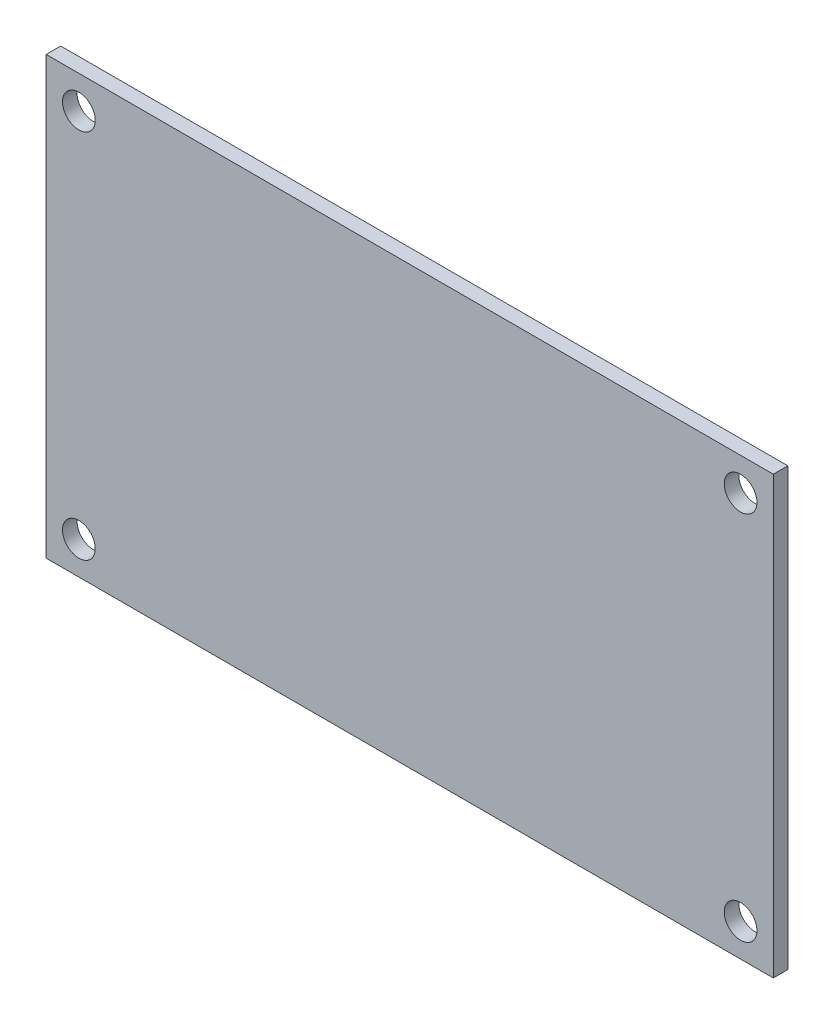
SolidWorks part; units mm, degrees
ref_plane "Front Plane" through (0, 0, 0) normal (0, 0, 1) x (1, 0, 0)
ref_plane "Top Plane" through (0, 0, 0) normal (0, 1, 0) x (1, 0, 0)
ref_plane "Right Plane" through (0, 0, 0) normal (1, 0, 0) x (0, 0, -1)
sketch "Sketch1" plane through (0, 0, 0) normal (0, 0, 1) x (1, 0, 0)
  line L1 (-50, 30) -> (50, 30)
  line L2 (-50, 30) -> (-50, -30)
  line L3 (-50, -30) -> (50, -30)
  line L4 (50, 30) -> (50, -30)
extrude "Boss-Extrude1" add sketch "Sketch1" along normal blind 2 contours L1 L4 L3 L2
hole_wizard "M4 Clearance Hole1" positions "3DSketch2" profile "Sketch4" hole size "M4" standard "ISO" end condition through all
sketch3d "3DSketch2"
  line L0 (-50, 30, 2) -> (-50, -30, 2) construction
  line L1 (-50, 30, 2) -> (50, 30, 2) construction
  line L2 (50, 30, 2) -> (50, -30, 2) construction
  line L3 (-50, -30, 2) -> (50, -30, 2) construction
  point P0 (-45.5, 25.5, 2)
  point P2 (-45.5, -25.5, 2)
  point P4 (45.5, -25.5, 2)
  point P6 (45.5, 25.5, 2)
  point P17 (0, 0, 0)
  point P18 (0, 0, 0)
  point P19 (0, 0, 0)
  point P20 (35.3071, 25, 2)
  point P21 (44.2725, 25, 2)
  point P22 (0, 0, 0)
  point P23 (0, 0, 0)
  point P24 (41.5036, 25, 2)
  dimension "D1" = 4.5
  dimension "D2" = 4.5
  dimension "D3" = 4.5
  dimension "D4" = 4.5
sketch "Sketch4" plane through (-45.5, 25.5, 2) normal (1, 0, 0) x (0, -1, 0)
  line L0 (0, 0) -> (0, 2)
  line L1 (0, 2) -> (2.25, 2)
  line L2 (2.25, 2) -> (2.25, 0)
  line L5 (2.25, 0) -> (0, 0)
  line L11 (0, -6.35) -> (0, 107.95) construction
  dimension "Thru Hole Dia." = 4.5
  dimension "Thru Hole Depth" = 2
